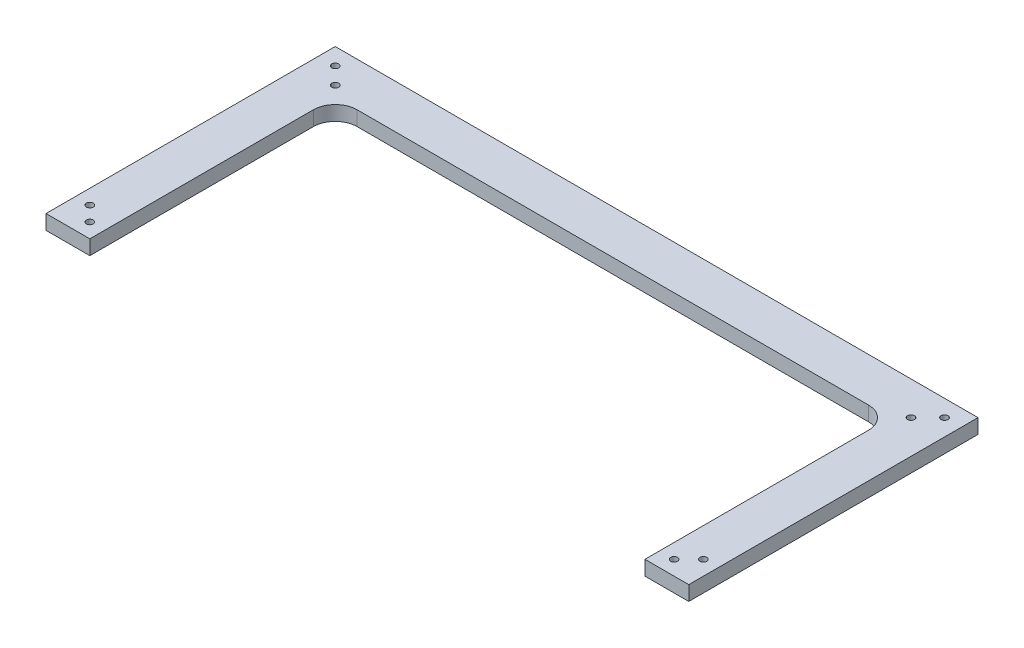
SolidWorks part; units mm, degrees
ref_plane "Front Plane" through (0, 0, 0) normal (0, 0, 1) x (1, 0, 0)
ref_plane "Top Plane" through (0, 0, 0) normal (0, 1, 0) x (1, 0, 0)
ref_plane "Right Plane" through (0, 0, 0) normal (1, 0, 0) x (0, 0, -1)
sketch "Sketch1" plane through (0, 0, 0) normal (0, 1, 0) x (1, 0, 0)
  line L0 (-120.65, -62.865) -> (-120.65, 43.815)
  line L1 (-139.7, -62.865) -> (-120.65, -62.865)
  line L2 (-139.7, -62.865) -> (-139.7, 62.865)
  line L3 (-139.7, 62.865) -> (139.7, 62.865)
  line L4 (139.7, -62.865) -> (139.7, 62.865)
  line L5 (-139.7, -62.865) -> (139.7, 62.865) construction
  line L6 (-139.7, 62.865) -> (139.7, -62.865) construction
  line L7 (-120.65, 43.815) -> (120.65, 43.815)
  line L8 (120.65, -62.865) -> (120.65, 43.815)
  line L9 (120.65, -62.865) -> (139.7, -62.865)
  point P0 (0, 0)
  dimension "D1" = 279.4
  dimension "D2" = 125.73
  dimension "D3" = 19.05
extrude "Boss-Extrude1" add sketch "Sketch1" against normal blind 6.35 contours L0 L7 L8 L9 L4 L3 L2 L1
fillet "Fillet1" radius 9.525 2 edges at (120.65, -3.175, -43.815) (-120.65, -3.175, -43.815)
sketch "Sketch2" plane through (0, 0, 0) normal (0, 1, 0) x (1, 0, 0)
  line L0 (-139.7, -43.815) -> (-120.65, -43.815) construction
  line L1 (132.4201, 55.5851) -> (139.7, 62.865) construction
  line L2 (0, 0) -> (0, -121.5954) construction
  line L3 (-139.7, -62.865) -> (-139.7, 62.865) construction
  line L4 (-120.65, -62.865) -> (-120.65, 34.29) construction
  line L5 (-120.65, -43.815) -> (-120.65, -62.865) construction
  line L6 (-139.7, -43.815) -> (-133.35, -50.165) construction
  line L7 (-133.35, -50.165) -> (-127, -56.515) construction
  line L8 (-127, -56.515) -> (-120.65, -62.865) construction
  line L9 (-117.8602, 41.0252) -> (-125.1401, 48.3051) construction
  line L10 (-125.1401, 48.3051) -> (-132.4201, 55.5851) construction
  line L11 (-132.4201, 55.5851) -> (-139.7, 62.865) construction
  line L12 (125.1401, 48.3051) -> (132.4201, 55.5851) construction
  line L13 (117.8602, 41.0252) -> (125.1401, 48.3051) construction
  line L14 (127, -56.515) -> (120.65, -62.865) construction
  line L19 (133.35, -50.165) -> (127, -56.515) construction
  line L21 (139.7, -43.815) -> (133.35, -50.165) construction
  line L22 (120.65, -43.815) -> (120.65, -62.865) construction
  line L23 (139.7, -43.815) -> (120.65, -43.815) construction
  circle A2 centre (-133.35, -50.165) radius 1.5
  circle A3 centre (-127, -56.515) radius 1.5
  circle A6 centre (-132.4201, 55.5851) radius 1.5
  circle A7 centre (-125.1401, 48.3051) radius 1.5
  arc A12 (-111.125, 43.815) -> (-120.65, 34.29) centre (-111.125, 34.29) ccw construction
  circle A13 centre (125.1401, 48.3051) radius 1.5
  circle A14 centre (132.4201, 55.5851) radius 1.5
  circle A15 centre (127, -56.515) radius 1.5
  circle A16 centre (133.35, -50.165) radius 1.5
  point P15 (-117.8602, 41.0252)
  dimension "D2" = 3
  dimension "D1" = 3
extrude "Cut-Extrude1" cut sketch "Sketch2" against normal through all
